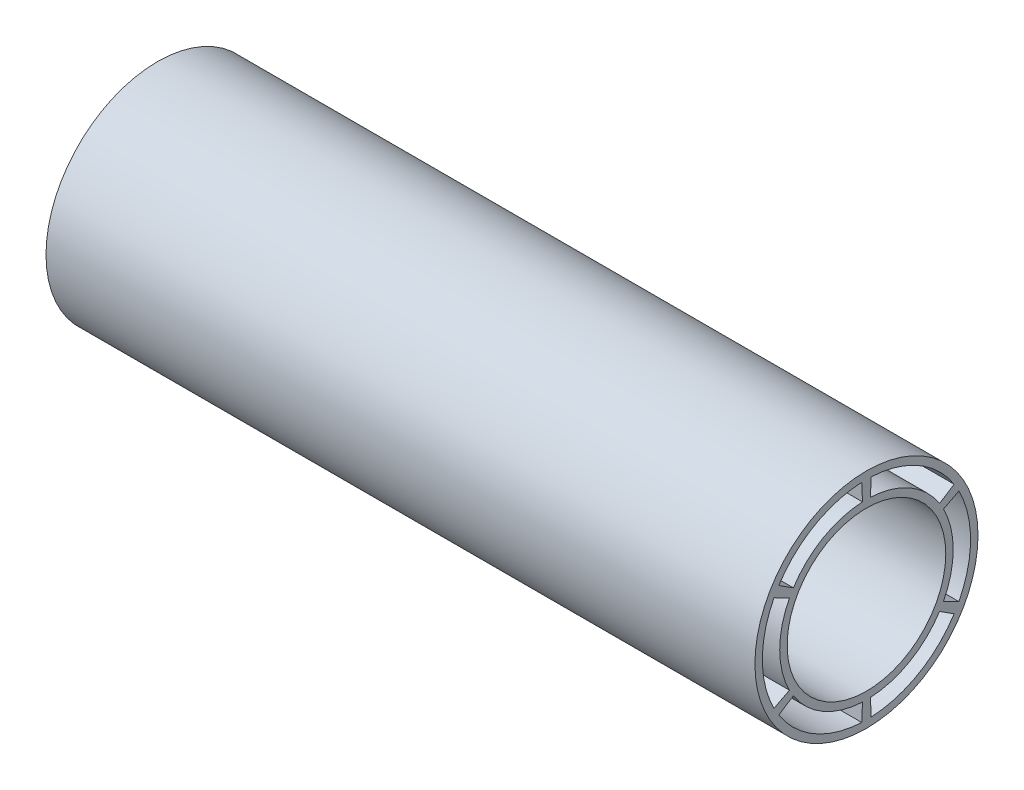
SolidWorks part; units mm, degrees
ref_plane "Front Plane" through (0, 0, 0) normal (0, 0, 1) x (1, 0, 0)
ref_plane "Top Plane" through (0, 0, 0) normal (0, 1, 0) x (1, 0, 0)
ref_plane "Right Plane" through (0, 0, 0) normal (1, 0, 0) x (0, 0, -1)
sketch "Sketch1" plane through (0, 0, 0) normal (1, 0, 0) x (0, 0, -1)
  line L0 (0, 0) -> (0, -21) construction
  line L1 (-15.5388, -8.0496) -> (-18.6465, -9.6595)
  line L2 (0.7982, -17.4818) -> (0.9579, -20.9781)
  line L3 (-0.7982, -17.4818) -> (-0.9579, -20.9781)
  line L4 (-14.7406, -9.4322) -> (-17.6887, -11.3186)
  line L5 (-14.7406, 9.4322) -> (-17.6887, 11.3186)
  line L6 (-15.5388, 8.0496) -> (-18.6465, 9.6595)
  line L7 (0.7982, 17.4818) -> (0.9579, 20.9781)
  line L8 (-0.7982, 17.4818) -> (-0.9579, 20.9781)
  line L9 (15.5388, 8.0496) -> (18.6465, 9.6595)
  line L10 (14.7406, 9.4322) -> (17.6887, 11.3186)
  line L11 (14.7406, -9.4322) -> (17.6887, -11.3186)
  line L12 (15.5388, -8.0496) -> (18.6465, -9.6595)
  circle A0 centre (0, 0) radius 22.5
  circle A1 centre (0, 0) radius 17.5
  circle A2 centre (0, 0) radius 21
  circle A3 centre (0, 0) radius 16
  circle A4 centre (0, 0) radius 21
  circle A5 centre (0, 0) radius 21
  circle A6 centre (0, 0) radius 21
  circle A7 centre (0, 0) radius 21
  circle A8 centre (0, 0) radius 21
  point P38 (0, 0)
  dimension "D1" = 45
  dimension "D2" = 35
  dimension "D3" = 42
  dimension "D4" = 32
  dimension "D5" = 6
extrude "Boss-Extrude1" add sketch "Sketch1" along normal blind 143
